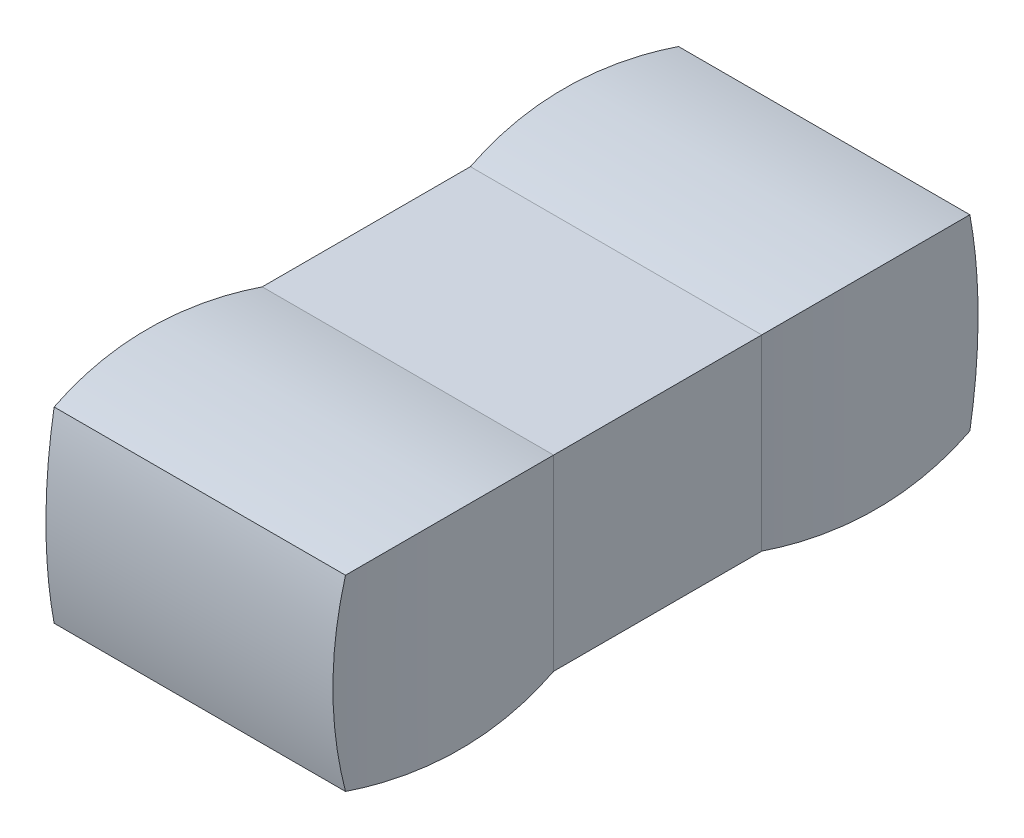
SolidWorks part; units mm, degrees
material "ASTM A36 Steel"
ref_plane "Front Plane" through (0, 0, 0) normal (0, 0, 1) x (1, 0, 0)
ref_plane "Top Plane" through (0, 0, 0) normal (0, 1, 0) x (1, 0, 0)
ref_plane "Right Plane" through (0, 0, 0) normal (1, 0, 0) x (0, 0, -1)
sketch "Sketch1" plane through (0, 0, 0) normal (1, 0, 0) x (0, 0, -1)
  line L0 (0.254, 0.2286) -> (-0.254, -0.2286) construction
  line L1 (-0.254, 0.2286) -> (0.254, 0.2286)
  line L2 (-0.254, 0.2286) -> (-0.254, -0.2286)
  line L3 (-0.254, -0.2286) -> (0.254, -0.2286)
  line L4 (0.254, 0.2286) -> (0.254, -0.2286)
  dimension "D2" = 0.4572
  dimension "D3" = 0.508
extrude "Boss-Extrude1" add sketch "Sketch1" along normal mid plane 0.7112
sketch "Sketch3" plane through (0, 0, 0) normal (1, 0, 0) x (0, 0, -1)
  line L0 (-0.254, 0.2286) -> (0.254, 0.2286) construction
  line L1 (-0.254, -0.2286) -> (0.254, -0.2286) construction
  line L2 (0.254, 0.2286) -> (0.254, -0.2286) construction
  line L3 (0.762, 0.2286) -> (0.762, -0.2286) construction
  line L4 (0.254, 0.2286) -> (0.254, -0.2286)
  arc A0 (0.254, 0.2286) -> (0.762, 0.2286) centre (0.508, -1.0287) cw
  arc A1 (0.254, -0.2286) -> (0.762, -0.2286) centre (0.508, 1.0287) ccw
  arc A2 (0.762, 0.2286) -> (0.762, -0.2286) centre (-0.254, 0) cw
  dimension "D1" = 0.0254
  dimension "D3" = 0.0254
  dimension "D2" = 0.508
extrude "Boss-Extrude3" add sketch "Sketch3" along normal mid plane 0.9144
sketch "Sketch4" plane through (0, 0, 0) normal (0, 1, 0) x (1, 0, 0)
  line L0 (0.3556, 0.254) -> (0.5826, 0.027)
  line L1 (0.5826, 0.027) -> (0.5826, 1.0805)
  line L2 (0.5826, 1.0805) -> (0.3383, 0.8362)
  line L3 (0.3556, 0.254) -> (0.3556, -0.3167) construction
  arc A0 (0.3556, 0.254) -> (0.3383, 0.8362) centre (-0.9017, 0.508) ccw
  point P5 (0.3556, 0.762)
  dimension "D2" = 0.0254
  dimension "D1" = 0.0762
  dimension "D3" = 0.508
  dimension "D4" = 45
extrude "Cut-Extrude1" cut sketch "Sketch4" against normal mid plane 0.9144
mirror "Mirror1" about plane through (0, 0, 0) normal (1, 0, 0) of "Cut-Extrude1"
mirror "Mirror2" about plane through (0, 0, 0) normal (0, 0, 1) of "Mirror1", "Cut-Extrude1", "Boss-Extrude3"
